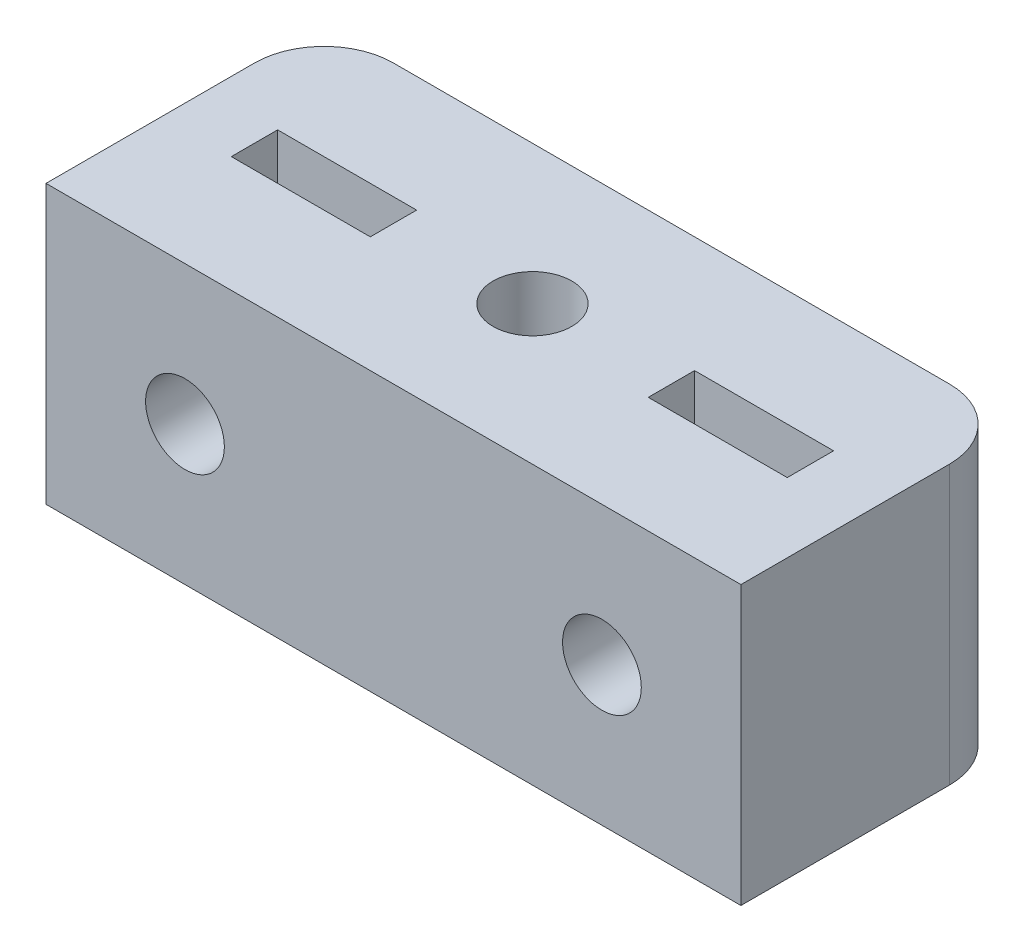
SolidWorks part; units mm, degrees
ref_plane "Front Plane" through (0, 0, 0) normal (0, 0, 1) x (1, 0, 0)
ref_plane "Top Plane" through (0, 0, 0) normal (0, 1, 0) x (1, 0, 0)
ref_plane "Right Plane" through (0, 0, 0) normal (1, 0, 0) x (0, 0, -1)
sketch "Sketch1" plane through (0, 0, 0) normal (0, 1, 0) x (1, 0, 0)
  line L1 (-15, -6) -> (15, -6)
  line L2 (-15, -6) -> (-15, 6)
  line L3 (-15, 6) -> (15, 6)
  line L4 (15, -6) -> (15, 6)
  line L5 (-15, -6) -> (15, 6) construction
  line L6 (-15, 6) -> (15, -6) construction
  point P0 (0, 0)
  dimension "D1" = 12
  dimension "D2" = 30
extrude "Boss-Extrude1" add sketch "Sketch1" along normal mid plane 12
sketch "Sketch2" plane through (0, 0, 6) normal (0, 0, 1) x (1, 0, 0)
  line L0 (-9, 6) -> (-9, -6) construction
  line L1 (-15, 6) -> (15, 6) construction
  line L3 (-15, 6) -> (-15, -6) construction
  line L4 (-15, -6) -> (15, -6) construction
  circle A0 centre (-9, 0) radius 1.7
  dimension "D2" = 3.4
  dimension "D1" = 6
extrude "Cut-Extrude1" cut sketch "Sketch2" against normal through all
sketch "Sketch3" plane through (0, 0, 0) normal (0, 0, 1) x (1, 0, 0)
  line L0 (-12, 3) -> (-12, 6)
  line L1 (-12, -3) -> (-6, -3)
  line L2 (-12, -3) -> (-12, 3)
  line L3 (-12, 3) -> (-6, 3) construction
  line L4 (-6, -3) -> (-6, 3)
  line L5 (-12, -3) -> (-6, 3) construction
  line L6 (-12, 3) -> (-6, -3) construction
  line L7 (-15, 6) -> (15, 6) construction
  line L8 (-12, 6) -> (-6, 6)
  line L9 (-6, 6) -> (-6, 3)
  circle A0 centre (-9, 0) radius 1.7 construction
  point P0 (-9, 0)
  dimension "D1" = 6
  dimension "D2" = 6
extrude "Cut-Extrude2" cut sketch "Sketch3" against normal mid plane 2
mirror "Mirror1" about plane through (0, 0, 0) normal (1, 0, 0) of "Cut-Extrude2", "Cut-Extrude1"
sketch "Sketch4" plane through (0, 6, 0) normal (0, 1, 0) x (1, 0, 0)
  circle A0 centre (0, 0) radius 1.7
  dimension "D1" = 3.4
extrude "Cut-Extrude3" cut sketch "Sketch4" against normal through all
sketch "Sketch5" plane through (0, 0, 0) normal (0, 1, 0) x (1, 0, 0)
  line L0 (-3, 3) -> (-3, 6)
  line L1 (-3, -3) -> (3, -3)
  line L2 (-3, -3) -> (-3, 3)
  line L3 (-3, 3) -> (3, 3) construction
  line L4 (3, -3) -> (3, 3)
  line L5 (-3, -3) -> (3, 3) construction
  line L6 (-3, 3) -> (3, -3) construction
  line L7 (15, 6) -> (-15, 6) construction
  line L8 (-3, 6) -> (3, 6)
  line L9 (3, 6) -> (3, 3)
  point P1 (0, 0)
  dimension "D1" = 6
  dimension "D2" = 6
extrude "Cut-Extrude4" cut sketch "Sketch5" against normal mid plane 2
fillet "Fillet1" radius 3 2 edges at (-15, 0, -6) (15, 0, -6)
equation "\"M3_d\"= 3.4"
equation "\"M3_nut_m\"= 2"
equation "\"M3_nut_s\"= 6"
equation "\"t\"= 3"
equation "\"D1@Sketch1\"=\"M3_nut_s\" + 2 * \"t\""
equation "\"D2@Sketch1\"=3 * \"M3_nut_s\" + 2 * \"t\" + 2 * \"t\""
equation "\"D1@Boss-Extrude1\"=\"M3_nut_s\" + 2 * \"t\""
equation "\"D1@Sketch2\"=\"t\" + \"M3_nut_s\" / 2 "
equation "\"D2@Sketch2\"=\"M3_d\""
equation "\"D1@Sketch3\"=\"M3_nut_s\""
equation "\"D2@Sketch3\"=\"M3_nut_s\""
equation "\"D1@Cut-Extrude2\"=\"M3_nut_m\""
equation "\"D1@Sketch4\"=\"M3_d\""
equation "\"D1@Sketch5\"=\"M3_nut_s\""
equation "\"D2@Sketch5\"=\"M3_nut_s\""
equation "\"D1@Cut-Extrude4\"=\"M3_nut_m\""
equation "\"D1@Fillet1\"=\"t\""
